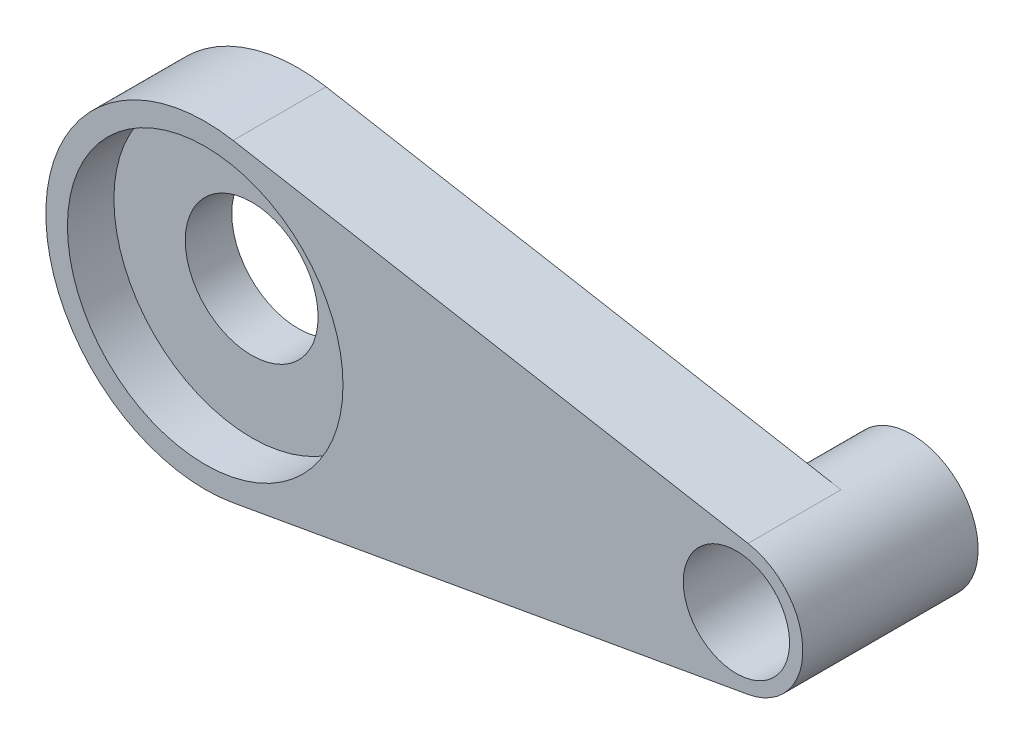
SolidWorks part; units mm, degrees
material "Vero PureWhite"
ref_plane "前视基准面" through (0, 0, 0) normal (0, 0, 1) x (1, 0, 0)
ref_plane "上视基准面" through (0, 0, 0) normal (0, 1, 0) x (1, 0, 0)
ref_plane "右视基准面" through (0, 0, 0) normal (1, 0, 0) x (0, 0, -1)
other "Configuration Table"
sketch "草图1" plane through (0, 0, 0) normal (0, 0, 1) x (1, 0, 0)
  line L0 (0, 0) -> (40, 0) construction
  line L1 (2.1, 11.8148) -> (40.875, 4.9228)
  line L2 (40.875, -4.9228) -> (2.1, -11.8148)
  arc A0 (2.1, 11.8148) -> (2.1, -11.8148) centre (0, 0) ccw
  arc A1 (40.875, 4.9228) -> (40.875, -4.9228) centre (40, 0) cw
  dimension "D2" = 12
  dimension "D3" = 5
  dimension "D1" = 40
extrude "凸台-拉伸1" add sketch "草图1" along normal blind 7
sketch "草图2" plane through (0, 0, 7) normal (0, 0, 1) x (1, 0, 0)
  circle A0 centre (0, 0) radius 10.375
  dimension "D1" = 20.75
extrude "切除-拉伸1" cut sketch "草图2" against normal blind 3.5
sketch "草图5" plane through (0, 0, 0) normal (0, 0, -1) x (-1, 0, 0)
sketch "草图6" plane through (0, 0, 0) normal (0, 0, -1) x (-1, 0, 0)
  circle A0 centre (0, 0) radius 5
  dimension "D1" = 10
extrude "切除-拉伸2" cut sketch "草图6" against normal through all
sketch "草图7" plane through (0, 0, 0) normal (0, 0, -1) x (-1, 0, 0)
sketch "草图8" plane through (0, 0, 0) normal (0, 0, -1) x (-1, 0, 0)
  circle A0 centre (-40, 0) radius 5
extrude "凸台-拉伸2" add sketch "草图8" along normal up to surface (6.2 mm away)
sketch "草图9" plane through (0, 0, 0) normal (0, 1, 0) x (1, 0, 0)
  line L0 (40, 14.45) -> (40, -14.0303) construction
  line L1 (42, 14.45) -> (38, 14.45) construction
  line L2 (40, 6.2) -> (38, 6.2)
  line L3 (45, 6.2) -> (35, 6.2) construction
  line L4 (38, 6.2) -> (38, 2.7)
  line L5 (38, 2.7) -> (36, 2.7)
  line L6 (36, 2.7) -> (36, -7)
  line L7 (2.1, -7) -> (40.875, -7) construction
  line L8 (36, -7) -> (40, -7)
  line L9 (40, 6.2) -> (40, -7)
  dimension "D1" = 4
  dimension "D2" = 8
  dimension "D3" = 3.5
revolve "切除-旋转1" cut sketch "草图9" angle 360 about L0
